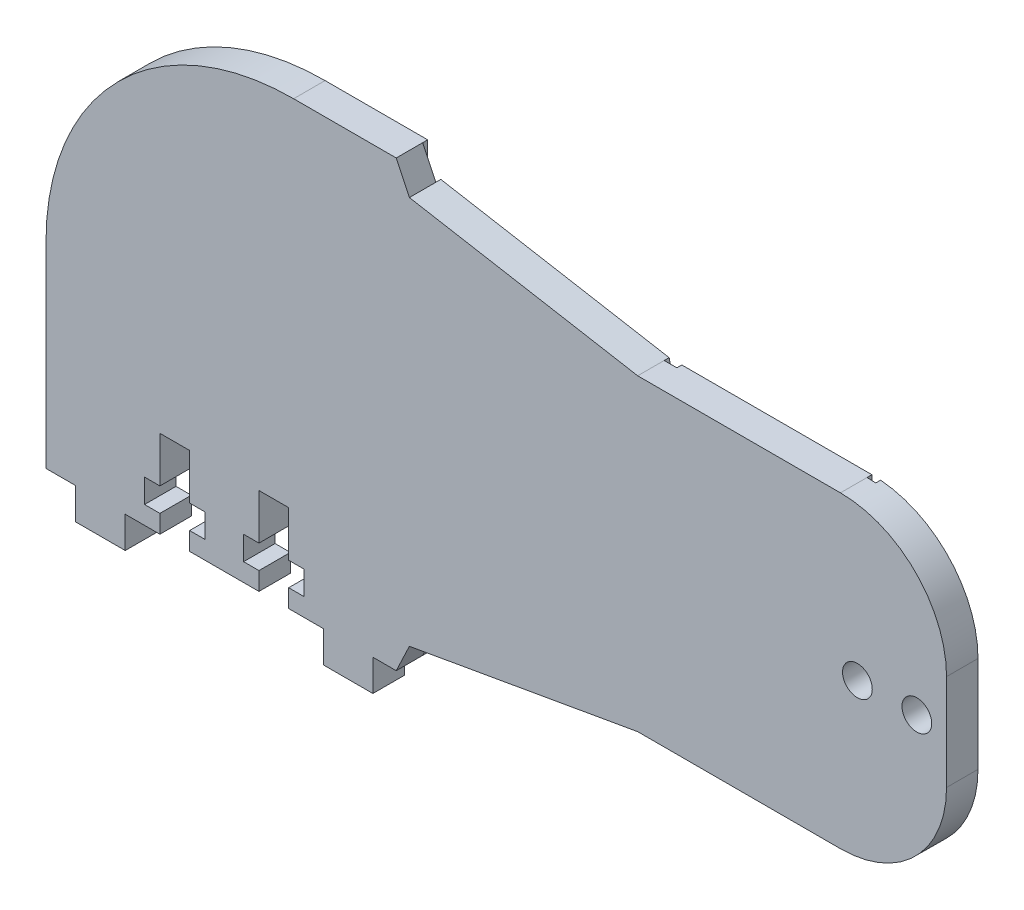
SolidWorks part; units mm, degrees
ref_plane "前视基准面" through (0, 0, 0) normal (0, 0, 1) x (1, 0, 0)
ref_plane "上视基准面" through (0, 0, 0) normal (0, 1, 0) x (1, 0, 0)
ref_plane "右视基准面" through (0, 0, 0) normal (1, 0, 0) x (0, 0, -1)
sketch "Sketch1" plane through (0, 0, 0) normal (0, 0, 1) x (1, 0, 0)
  line L0 (-343.602, 79.5824) -> (229.7313, 79.5824) construction
  line L1 (37.2968, 22.4039) -> (96.4792, 22.4039) construction
  line L7 (70.6851, 37.9618) -> (50.2151, 37.9618)
  line L8 (50.2151, 37.9618) -> (27.1662, 42.0199)
  line L9 (81.3972, 22.4039) -> (81.3972, 17.5582)
  line L11 (27.1662, 42.0199) -> (25.8378, 44.8177)
  line L12 (25.8378, 44.8177) -> (-9.5188, 44.8177)
  line L13 (81.3972, 22.4039) -> (81.3972, 27.2497)
  line L14 (27.1662, 2.788) -> (25.8378, -0.0098)
  line L15 (50.2151, 6.8461) -> (27.1662, 2.788)
  line L16 (70.6851, 6.8461) -> (50.2151, 6.8461)
  line L18 (25.8378, -0.0098) -> (-9.5188, -0.0098)
  line L20 (-9.5188, 44.8177) -> (-9.5188, -0.0098)
  arc A0 (81.3972, 27.2497) -> (70.6851, 37.9618) centre (70.6851, 27.2497) ccw
  arc A1 (81.3972, 17.5582) -> (70.6851, 6.8461) centre (70.6851, 17.5582) cw
extrude "Boss-Extrude1" add sketch "Sketch1" along normal blind 3.175
sketch "Sketch2" plane through (0, 0, 3.175) normal (0, 0, 1) x (1, 0, 0)
  line L0 (8.4812, 7.6148) -> (8.4812, -13.2615) construction
  line L1 (-4.0188, -3.1848) -> (-4.0188, 0.254) construction
  line L2 (20.9812, -3.1848) -> (20.9812, 0.254) construction
  line L3 (-9.5188, 44.8177) -> (-9.5188, -0.0098) construction
  line L4 (-6.5188, -0.0098) -> (-1.5188, -0.0098)
  line L5 (-9.5188, -0.0098) -> (25.8378, -0.0098) construction
  line L6 (-1.5188, -0.0098) -> (-1.5188, -3.1848)
  line L7 (-1.5188, -3.1848) -> (-6.5188, -3.1848)
  line L8 (-6.5188, -3.1848) -> (-6.5188, -0.0098)
  line L9 (23.4812, -3.1848) -> (23.4812, -0.0098)
  line L10 (18.4812, -3.1848) -> (23.4812, -3.1848)
  line L11 (18.4812, -0.0098) -> (18.4812, -3.1848)
  line L12 (23.4812, -0.0098) -> (18.4812, -0.0098)
  dimension "D1" = 18
  dimension "D2" = 3.175
  dimension "D3" = 5
  dimension "D4" = 25
extrude "Boss-Extrude2" add sketch "Sketch2" against normal blind 3.175
sketch "Sketch3" plane through (0, 0, 3.175) normal (0, 0, 1) x (1, 0, 0)
  line L0 (8.4812, -0.0098) -> (8.4812, 18.1235) construction
  line L1 (-1.5188, -0.0098) -> (18.4812, -0.0098) construction
  line L2 (3.4812, 5.3129) -> (3.4812, -3.9514) construction
  line L3 (4.9812, -0.0098) -> (1.9812, -0.0098)
  line L4 (1.9812, -0.0098) -> (1.9812, 1.8152)
  line L5 (1.9812, 1.8152) -> (0.4312, 1.8152)
  line L6 (0.4312, 1.8152) -> (0.4312, 4.2152)
  line L7 (0.4312, 4.2152) -> (1.9812, 4.2152)
  line L8 (1.9812, 4.2152) -> (1.9812, 8.8152)
  line L9 (1.9812, 8.8152) -> (4.9812, 8.8152)
  line L10 (4.9812, 4.2152) -> (4.9812, 8.8152)
  line L11 (6.5312, 4.2152) -> (4.9812, 4.2152)
  line L12 (6.5312, 1.8152) -> (6.5312, 4.2152)
  line L13 (4.9812, 1.8152) -> (6.5312, 1.8152)
  line L14 (4.9812, -0.0098) -> (4.9812, 1.8152)
  line L15 (-6.5188, -3.1848) -> (-1.5188, -3.1848) construction
  line L16 (13.4812, 5.3129) -> (13.4812, -3.9514) construction
  line L17 (11.9812, -0.0098) -> (11.9812, 1.8152)
  line L18 (11.9812, 1.8152) -> (10.4312, 1.8152)
  line L19 (10.4312, 1.8152) -> (10.4312, 4.2152)
  line L20 (10.4312, 4.2152) -> (11.9812, 4.2152)
  line L21 (11.9812, 4.2152) -> (11.9812, 8.8152)
  line L22 (14.9812, 8.8152) -> (11.9812, 8.8152)
  line L23 (14.9812, 4.2152) -> (14.9812, 8.8152)
  line L24 (16.5312, 4.2152) -> (14.9812, 4.2152)
  line L25 (16.5312, 1.8152) -> (16.5312, 4.2152)
  line L26 (14.9812, 1.8152) -> (16.5312, 1.8152)
  line L27 (14.9812, -0.0098) -> (14.9812, 1.8152)
  line L28 (11.9812, -0.0098) -> (14.9812, -0.0098)
  point P15 (3.4812, 8.8152)
  point P20 (3.4812, -0.0098)
  point P36 (13.4812, -0.0098)
  point P37 (13.4812, 8.8152)
  dimension "D1" = 6.1
  dimension "D2" = 2.4
  dimension "D3" = 12
  dimension "D4" = 5
  dimension "D5" = 3
  dimension "D6" = 10
extrude "Cut-Extrude1" cut sketch "Sketch3" against normal through all
sketch "Sketch4" plane through (0, 0, 0) normal (0, 0, 1) x (1, 0, 0)
  line L0 (81.3972, 22.4039) -> (-12.0004, 22.4039) construction
  line L1 (81.3972, 17.5582) -> (81.3972, 27.2497) construction
  line L2 (70.6851, 37.9618) -> (50.2151, 37.9618) construction
  line L3 (50.2151, 6.8461) -> (70.6851, 6.8461) construction
  line L4 (50.2151, 37.9618) -> (51.4958, 37.9618)
  line L5 (50.2151, 6.8461) -> (51.4958, 6.8461)
  line L8 (27.1662, 42.0199) -> (27.1662, 2.788)
  line L9 (25.8378, 44.8177) -> (25.8378, -0.0098)
  line L10 (27.1662, 2.788) -> (50.2151, 6.8461) construction
  line L11 (27.1662, 2.788) -> (25.8378, -0.0098)
  line L12 (25.8378, 44.8177) -> (27.1662, 42.0199)
  line L13 (70.6851, 37.9618) -> (70.6851, 6.8461)
  line L14 (71.5663, 37.9255) -> (71.5663, 6.8824)
  arc A0 (50.2151, 37.9618) -> (50.2151, 6.8461) centre (-5.5875, 22.4039) cw
  arc A1 (51.4958, 37.9618) -> (51.4958, 6.8461) centre (-5.7887, 22.4039) cw
  arc A9 (70.6851, 6.8461) -> (81.3972, 17.5582) centre (70.6851, 17.5582) ccw construction
  arc A10 (70.6851, 6.8461) -> (71.5663, 6.8824) centre (70.6851, 17.5582) ccw
  arc A11 (81.3972, 27.2497) -> (70.6851, 37.9618) centre (70.6851, 27.2497) ccw construction
  arc A12 (71.5663, 37.9255) -> (70.6851, 37.9618) centre (70.6851, 27.2497) ccw
extrude "Cut-Extrude4" cut sketch "Sketch4" along normal blind 0.5
sketch "Sketch5" plane through (0, 0, 3.175) normal (0, 0, 1) x (1, 0, 0)
  line L0 (25.8378, 44.8177) -> (-9.5188, 44.8177) construction
  line L1 (-9.5188, 44.8177) -> (-9.5188, -0.0098) construction
  line L2 (15.4812, 44.8177) -> (-9.5188, 44.8177)
  line L3 (-9.5188, 44.8177) -> (-9.5188, 19.8177)
  arc A0 (15.4812, 44.8177) -> (-9.5188, 19.8177) centre (15.4812, 19.8177) ccw
  dimension "D1" = 25
extrude "Cut-Extrude5" cut sketch "Sketch5" against normal through all
sketch "Sketch6" plane through (0, 0, 3.175) normal (0, 0, 1) x (1, 0, 0)
  line L0 (81.3972, 22.4039) -> (64.5233, 22.4039) construction
  line L1 (81.3972, 17.5582) -> (81.3972, 27.2497) construction
  circle A0 centre (78.3972, 22.4039) radius 1.5
  circle A1 centre (72.3972, 22.4039) radius 1.5
  dimension "D1" = 3
  dimension "D2" = 3
  dimension "D3" = 6
  dimension "D4" = 3
extrude "Cut-Extrude6" cut sketch "Sketch6" against normal through all
